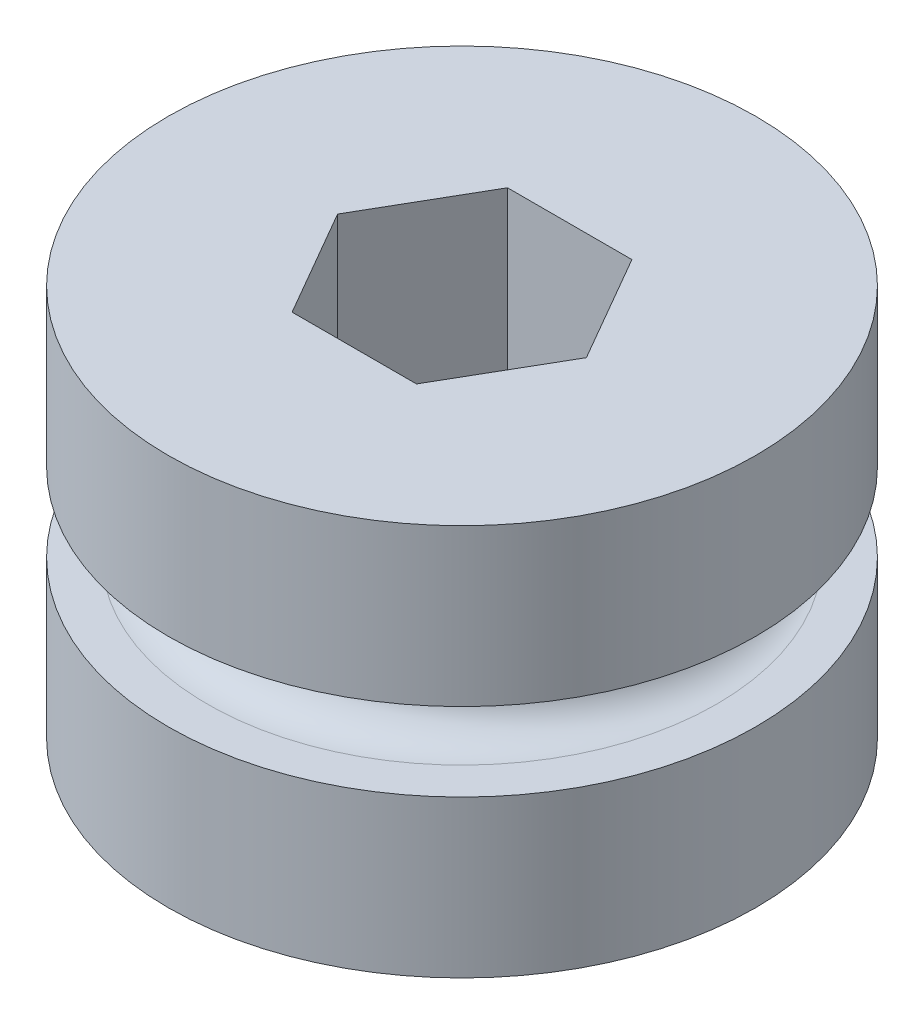
SolidWorks part; units mm, degrees
ref_plane "Front Plane" through (0, 0, 0) normal (0, 0, 1) x (1, 0, 0)
ref_plane "Top Plane" through (0, 0, 0) normal (0, 1, 0) x (1, 0, 0)
ref_plane "Right Plane" through (0, 0, 0) normal (1, 0, 0) x (0, 0, -1)
sketch "Sketch2" plane through (0, 0, 0) normal (0, 1, 0) x (1, 0, 0)
  circle A0 centre (0, 0) radius 19.05
  dimension "D1" = 38.1
extrude "Boss-Extrude1" add sketch "Sketch2" along normal blind 25.4
sketch "Sketch4" plane through (0, 0, 0) normal (0, 0, 1) x (1, 0, 0)
  line L0 (-19.05, 25.4) -> (-19.05, 0) construction
  line L1 (-19.05, 0) -> (19.05, 0) construction
  line L2 (-16.51, 15.24) -> (-19.05, 15.24)
  line L3 (-19.05, 15.24) -> (-19.05, 10.16)
  line L4 (-19.05, 10.16) -> (-16.51, 10.16)
  arc A0 (-16.51, 15.24) -> (-16.51, 10.16) centre (-16.51, 12.7) cw
  dimension "D1" = 5.08
  dimension "D2" = 2.54
  dimension "D3" = 2.54
  dimension "D4" = 12.7
sketch "Sketch5" plane through (0, 0, 0) normal (0, 0, 1) x (1, 0, 0)
  line L0 (0, 0) -> (0, 25.4) construction
  line L1 (19.05, 25.4) -> (-19.05, 25.4) construction
revolve "Cut-Revolve2" cut sketch "Sketch4" angle 360 about L0
sketch "Sketch7" plane through (0, 25.4, 0) normal (0, 1, 0) x (1, 0, 0)
  line L1 (8.0656, 0) -> (4.0328, 6.985)
  line L2 (4.0328, 6.985) -> (-4.0328, 6.985)
  line L3 (-4.0328, 6.985) -> (-8.0656, 0)
  line L4 (-8.0656, 0) -> (-4.0328, -6.985)
  line L5 (-4.0328, -6.985) -> (4.0328, -6.985)
  line L6 (4.0328, -6.985) -> (8.0656, 0)
  circle A0 centre (0, 0) radius 6.985 construction
  dimension "D1" = 6.985
extrude "Cut-Extrude1" cut sketch "Sketch7" against normal through all
